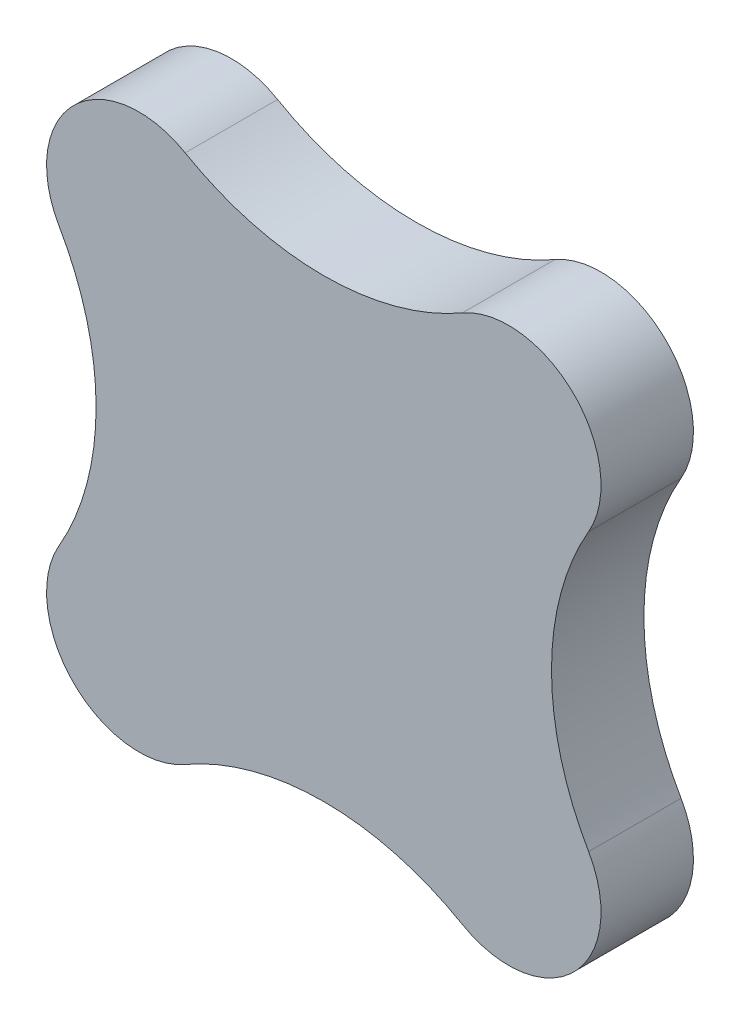
SolidWorks part; units mm, degrees
ref_plane "정면" through (0, 0, 0) normal (0, 0, 1) x (1, 0, 0)
ref_plane "윗면" through (0, 0, 0) normal (0, 1, 0) x (1, 0, 0)
ref_plane "우측면" through (0, 0, 0) normal (1, 0, 0) x (0, 0, -1)
sketch "스케치1" plane through (0, 0, 0) normal (0, 0, 1) x (1, 0, 0)
  line L0 (-25.4, 0) -> (25.4, 0) construction
  line L1 (0, 25.4) -> (0, -25.4) construction
  arc A0 (-19.05, 36.3985) -> (-36.3985, 19.05) centre (-25.4, 25.4) ccw
  arc A1 (-36.3985, 19.05) -> (-36.3985, -19.05) centre (-69.3941, 0) cw
  arc A2 (-19.05, 36.3985) -> (19.05, 36.3985) centre (0, 69.3941) ccw
  arc A3 (-19.05, -36.3985) -> (-36.3985, -19.05) centre (-25.4, -25.4) cw
  arc A4 (-19.05, -36.3985) -> (19.05, -36.3985) centre (0, -69.3941) cw
  arc A5 (19.05, -36.3985) -> (36.3985, -19.05) centre (25.4, -25.4) ccw
  arc A6 (36.3985, 19.05) -> (36.3985, -19.05) centre (69.3941, 0) ccw
  arc A7 (19.05, 36.3985) -> (36.3985, 19.05) centre (25.4, 25.4) cw
  point P4 (0, 0)
  point P8 (0, 0)
  point P12 (0, 0)
  point P13 (0, 0)
  point P14 (0, 0)
  point P15 (0, 0)
  point P16 (0, 0)
  point P20 (0, 28.6394)
  point P21 (-31.2941, 0)
  dimension "D1" = 12.7
  dimension "D4" = 38.1
  dimension "D2" = 50.8
  dimension "D3" = 50.8
extrude "보스-돌출1" add sketch "스케치1" against normal blind 12.7
